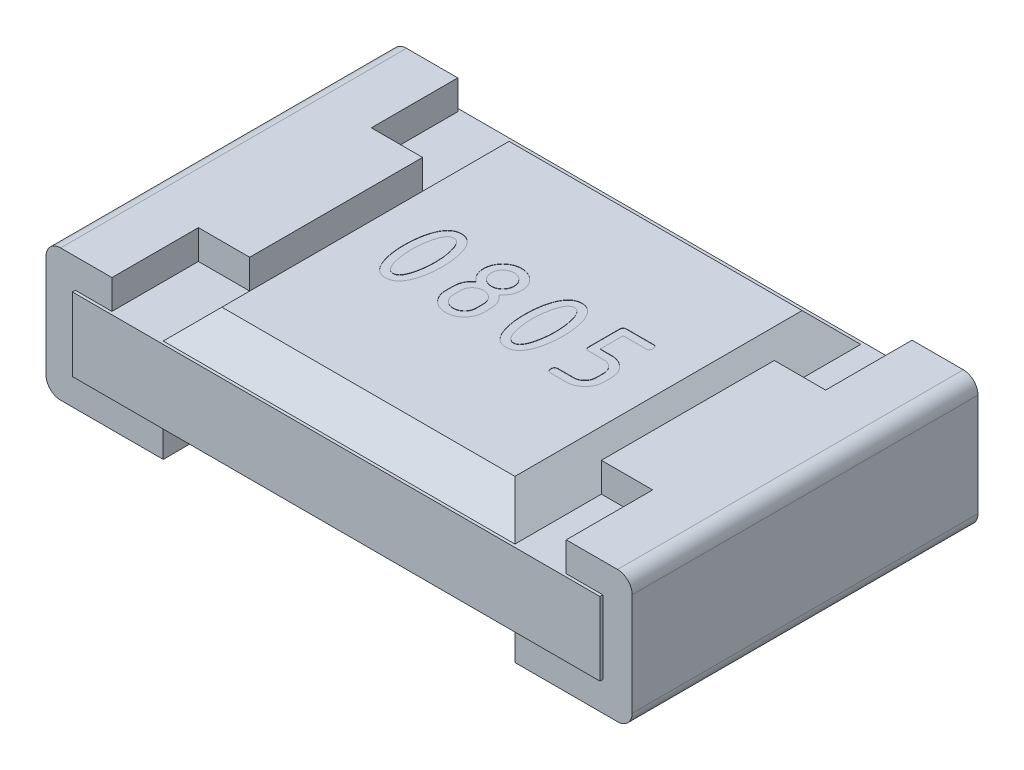
SolidWorks part; units mm, degrees
ref_plane "Front" through (0, 0, 0) normal (0, 0, 1) x (1, 0, 0)
ref_plane "Top" through (0, 0, 0) normal (0, 1, 0) x (1, 0, 0)
ref_plane "Right" through (0, 0, 0) normal (1, 0, 0) x (0, 0, -1)
sketch "Sketch1" plane through (0, 0, 0) normal (0, 1, 0) x (1, 0, 0)
  line L1 (-0.9, -0.6) -> (0.9, -0.6)
  line L2 (-0.9, -0.6) -> (-0.9, 0.6)
  line L3 (-0.9, 0.6) -> (0.9, 0.6)
  line L4 (0.9, -0.6) -> (0.9, 0.6)
  line L5 (-0.9, -0.6) -> (0.9, 0.6) construction
  line L6 (-0.9, 0.6) -> (0.9, -0.6) construction
  point P0 (0, 0)
  dimension "D1" = 1.8
  dimension "D2" = 1.2
extrude "Boss-Extrude1" add sketch "Sketch1" along normal mid plane 0.25
sketch "Sketch2" plane through (0, 0, 0) normal (0, 1, 0) x (1, 0, 0)
  line L0 (-1, 0.59) -> (-0.6, 0.59)
  line L1 (0.9, 0.6) -> (-0.9, 0.6) construction
  line L2 (-0.6, 0.59) -> (-0.6, -0.59)
  line L8 (-0.6, -0.59) -> (-1, -0.59)
  line L9 (-1, -0.59) -> (-1, 0.59)
  line L11 (0, 0) -> (0, 0.6) construction
  line L20 (0, 0) -> (-0.6, 0) construction
  line L21 (-0.6, 0) -> (-1, 0) construction
  line L37 (1, -0.59) -> (1, 0.59)
  line L38 (0.6, -0.59) -> (1, -0.59)
  line L39 (0.6, 0.59) -> (0.6, -0.59)
  line L40 (1, 0.59) -> (0.6, 0.59)
  dimension "D1" = 2
  dimension "D2" = 1.2
  dimension "D5" = 1.18
extrude "Boss-Extrude2" add sketch "Sketch2" along normal mid plane 0.45
fillet "Fillet1" radius 0.05 4 edges at (-1, -0.225, 0) (-1, 0.225, 0) (1, -0.225, 0) (1, 0.225, 0)
sketch "Sketch6" plane through (0, 0.225, 0) normal (0, 1, 0) x (1, 0, 0)
  line L0 (-0.6, 0.59) -> (-0.95, 0.59) construction
  line L1 (-0.775, 0.59) -> (0.775, 0.59)
  line L2 (-0.775, 0.59) -> (-0.775, 0.295)
  line L3 (-0.775, 0.295) -> (0.775, 0.295)
  line L4 (0.775, 0.59) -> (0.775, 0.295)
  line L5 (-0.95, -0.59) -> (-0.6, -0.59) construction
  line L6 (-0.775, -0.59) -> (0.775, -0.59)
  line L7 (-0.775, -0.59) -> (-0.775, -0.295)
  line L8 (-0.775, -0.295) -> (0.775, -0.295)
  line L9 (0.775, -0.59) -> (0.775, -0.295)
  line L10 (0.6, -0.59) -> (0.95, -0.59) construction
  line L11 (-0.775, 0.295) -> (-0.775, 0) construction
  line L12 (-0.775, 0) -> (-0.775, -0.295) construction
extrude "Cut-Extrude2" cut sketch "Sketch6" against normal up to surface (0.1 mm away) up to face at (0, 0.125, 0)
sketch "Sketch4" plane through (0, 0.125, 0) normal (0, 1, 0) x (1, 0, 0)
  line L0 (0.6, 0.295) -> (0.6, -0.295) construction
  line L5 (-0.775, 0.59) -> (-0.9, 0.59) construction
  line L6 (-0.6, -0.59) -> (0.6, -0.59)
  line L8 (-0.6, -0.59) -> (-0.6, 0.59)
  line L9 (-0.6, 0.59) -> (0.6, 0.59)
  line L10 (0.6, -0.59) -> (0.6, 0.59)
  line L11 (-0.6, -0.59) -> (0.6, 0.59) construction
  line L12 (-0.6, 0.59) -> (0.6, -0.59) construction
  point P0 (0, 0)
extrude "Boss-Extrude3" add sketch "Sketch4" along normal up to surface (0.1 mm away) draft 45
sketch "Sketch5" plane through (0, 0.225, 0) normal (0, 1, 0) x (1, 0, 0)
  line L0 (-0.5, -0.1239) -> (0.5, -0.1239) construction
  line L1 (-0.5, 0.49) -> (-0.5, -0.49) construction
  line L2 (0.5, -0.49) -> (0.5, 0.49) construction
  text T0 "0805" font "ISOCPEUR" height 0.26
  point P7 (-0.5, -0.1239)
extrude "Cut-Extrude1" cut sketch "Sketch5" against normal blind 0.001
